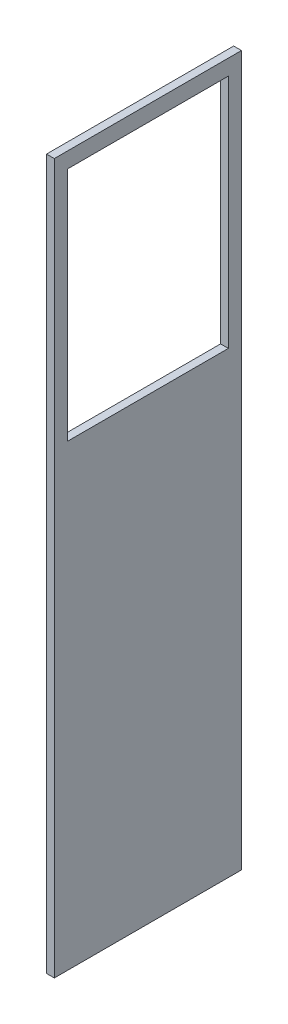
SolidWorks part; units mm, degrees
ref_plane "Front Plane" through (0, 0, 0) normal (0, 0, 1) x (1, 0, 0)
ref_plane "Top Plane" through (0, 0, 0) normal (0, 1, 0) x (1, 0, 0)
ref_plane "Right Plane" through (0, 0, 0) normal (1, 0, 0) x (0, 0, -1)
sketch "Sketch1" plane through (0, 0, 0) normal (1, 0, 0) x (0, 0, -1)
  line L1 (0, 0) -> (76.2, 0)
  line L2 (0, 0) -> (0, 288.925)
  line L3 (0, 288.925) -> (76.2, 288.925)
  line L4 (76.2, 0) -> (76.2, 288.925)
  dimension "D1" = 76.2
  dimension "D2" = 288.925
extrude "Boss-Extrude1" add sketch "Sketch1" along normal blind 3.175
ref_plane "Plane1" through (0, 0, -38.1) normal (0, 0, -1) x (-1, 0, 0)
sketch "Sketch2" plane through (0, 0, 0) normal (-1, 0, 0) x (0, 0, 1)
  line L1 (-70.866, 186.563) -> (-5.334, 186.563)
  line L2 (-70.866, 186.563) -> (-70.866, 282.575)
  line L3 (-70.866, 282.575) -> (-5.334, 282.575)
  line L4 (-5.334, 186.563) -> (-5.334, 282.575)
  line L6 (-76.2, 288.925) -> (0, 288.925) construction
  point P6 (-38.1, 288.925)
  point P7 (-38.1, 282.575)
  dimension "D1" = 96.012
  dimension "D2" = 65.532
  dimension "D3" = 6.35
extrude "Cut-Extrude1" cut sketch "Sketch2" against normal up to next
